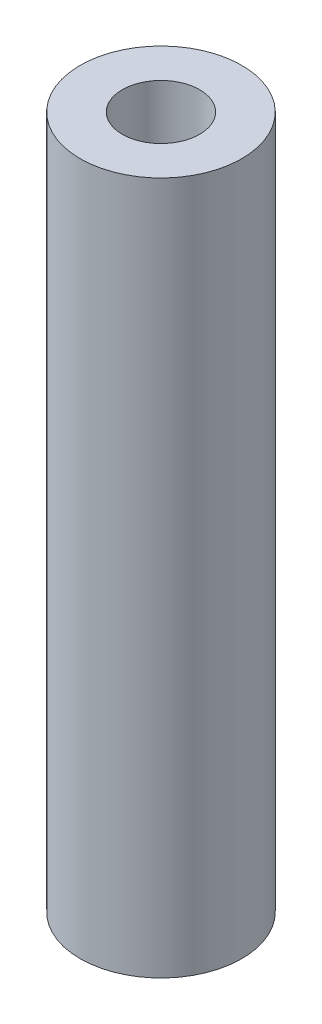
SolidWorks part; units mm, degrees
ref_plane "Front Plane" through (0, 0, 0) normal (0, 0, 1) x (1, 0, 0)
ref_plane "Top Plane" through (0, 0, 0) normal (0, 1, 0) x (1, 0, 0)
ref_plane "Right Plane" through (0, 0, 0) normal (1, 0, 0) x (0, 0, -1)
sketch "Sketch1" plane through (0, 0, 0) normal (0, 1, 0) x (1, 0, 0)
  circle A0 centre (0, 0) radius 3.5
  circle A1 centre (0, 0) radius 1.675
  dimension "D1" = 7
  dimension "D2" = 3.35
extrude "Boss-Extrude1" add sketch "Sketch1" along normal blind 30
ref_plane "Plane1" through (3.5, 0, 0) normal (1, 0, 0) x (0, 0, -1)
sketch "Sketch2" plane through (3.5, 0, 0) normal (1, 0, 0) x (0, 0, -1)
  line L0 (3.5, 15) -> (-3.5, 15) construction
  line L1 (3.5, 0) -> (3.5, 30) construction
  line L2 (-3.5, 30) -> (-3.5, 0) construction
  line L3 (-3.5, 0) -> (3.5, 0) construction
  line L4 (-2.875, 8.5) -> (2.875, 8.5)
  line L5 (-2.875, 8.5) -> (-2.875, 5.5)
  line L6 (-2.875, 5.5) -> (2.875, 5.5)
  line L7 (2.875, 8.5) -> (2.875, 5.5)
  line L8 (-2.875, 21.5) -> (-2.875, 24.5)
  line L9 (2.875, 21.5) -> (2.875, 24.5)
  line L10 (-2.875, 24.5) -> (2.875, 24.5)
  line L11 (-2.875, 21.5) -> (2.875, 21.5)
  point P10 (0, 5.5)
  point P14 (2.875, 7)
  dimension "D1" = 5.75
  dimension "D2" = 3
  dimension "D3" = 7
